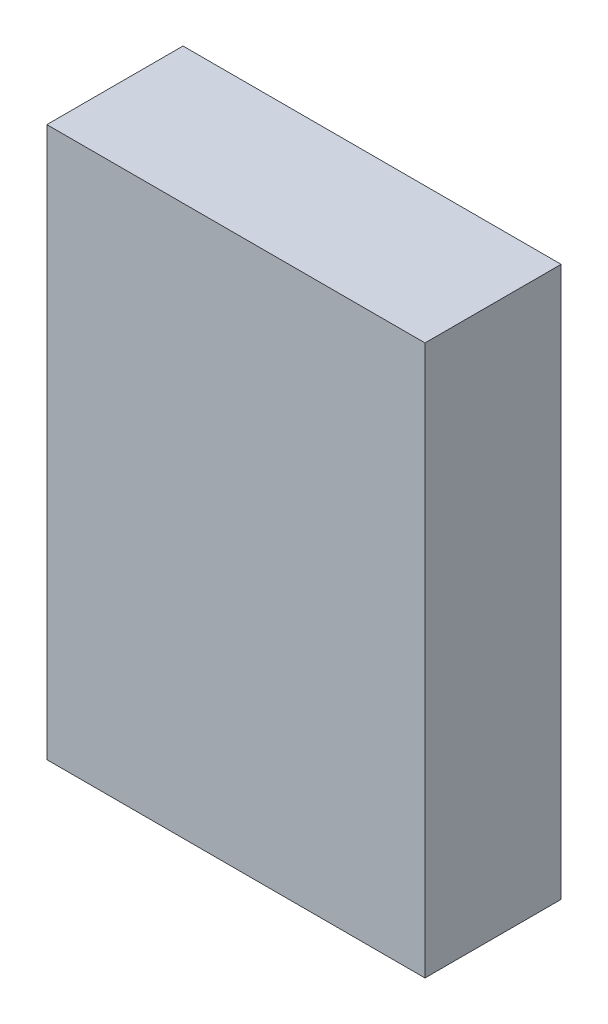
SolidWorks part; units mm, degrees
material "Ferro duttile (SN)"
ref_plane "Piano frontale" through (0, 0, 0) normal (0, 0, 1) x (1, 0, 0)
ref_plane "Piano superiore" through (0, 0, 0) normal (0, 1, 0) x (1, 0, 0)
ref_plane "Piano destro" through (0, 0, 0) normal (1, 0, 0) x (0, 0, -1)
sketch "Schizzo1" plane through (0, 0, 0) normal (0, 0, 1) x (1, 0, 0)
  line L1 (-55, 80) -> (55, 80)
  line L2 (-55, 80) -> (-55, -80)
  line L3 (-55, -80) -> (55, -80)
  line L4 (55, 80) -> (55, -80)
  line L5 (-55, 80) -> (55, -80) construction
  line L6 (-55, -80) -> (55, 80) construction
  point P0 (0, 0)
  dimension "D1" = 110
  dimension "D2" = 160
extrude "Estrusione-Estrusione2" add sketch "Schizzo1" along normal blind 3.6 and the other way blind 36
shell "Svuota3" thickness 1
sketch "Schizzo32" plane through (0, 0, -35) normal (0, 0, 1) x (1, 0, 0)
  line L0 (55, -80) -> (55, 80) construction
  line L1 (-55, 80) -> (55, 80)
  line L2 (-55, 80) -> (-55, 79)
  line L3 (-55, 79) -> (55, 79)
  line L4 (55, 80) -> (55, 79)
  dimension "D1" = 1
extrude "Estrusione-Estrusione3" add sketch "Schizzo32" along normal up to next
